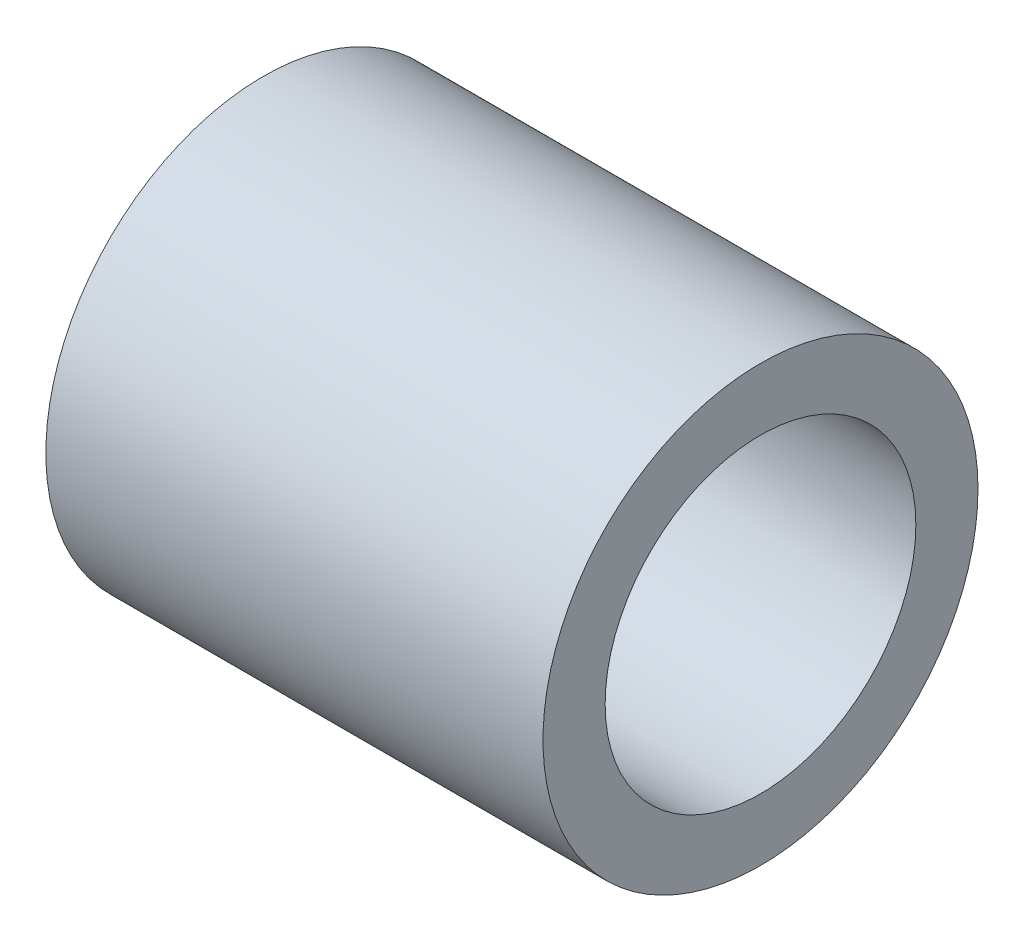
SolidWorks part; units mm, degrees
ref_plane "Front Plane" through (0, 0, 0) normal (0, 0, 1) x (1, 0, 0)
ref_plane "Top Plane" through (0, 0, 0) normal (0, 1, 0) x (1, 0, 0)
ref_plane "Right Plane" through (0, 0, 0) normal (1, 0, 0) x (0, 0, -1)
sketch "Sketch1" plane through (0, 0, 0) normal (1, 0, 0) x (0, 0, -1)
  circle A0 centre (0, 0) radius 12.5
  circle A1 centre (0, 0) radius 17.5
extrude "Boss-Extrude1" add sketch "Sketch1" along normal mid plane 40
